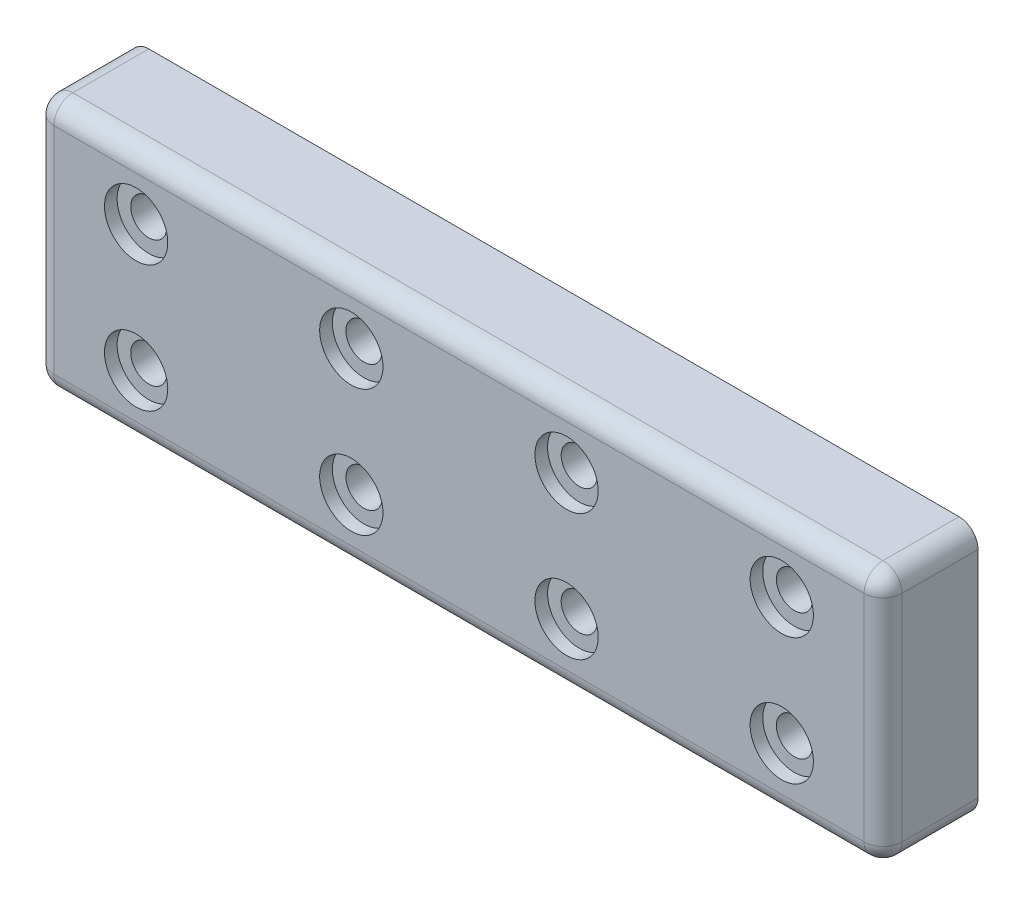
SolidWorks part; units mm, degrees
ref_plane "Front Plane" through (0, 0, 0) normal (0, 0, 1) x (1, 0, 0)
ref_plane "Top Plane" through (0, 0, 0) normal (0, 1, 0) x (1, 0, 0)
ref_plane "Right Plane" through (0, 0, 0) normal (1, 0, 0) x (0, 0, -1)
sketch "Sketch1" plane through (0, 0, 0) normal (0, 0, 1) x (1, 0, 0)
  line L1 (-67, -20) -> (67, -20)
  line L2 (-67, -20) -> (-67, 20)
  line L3 (-67, 20) -> (67, 20)
  line L4 (67, -20) -> (67, 20)
  line L5 (-67, -20) -> (67, 20) construction
  line L6 (-67, 20) -> (67, -20) construction
  circle A0 centre (-51, 10) radius 2.85
  circle A1 centre (-17, 10) radius 2.85
  circle A2 centre (17, 10) radius 2.85
  circle A3 centre (51, 10) radius 2.85
  circle A4 centre (-17, -10) radius 2.85
  circle A5 centre (17, -10) radius 2.85
  circle A6 centre (51, -10) radius 2.85
  circle A7 centre (-51, -10) radius 2.85
  point P0 (0, 0)
  dimension "D3" = 5.7
  dimension "D1" = 134
  dimension "D2" = 40
  dimension "D4" = 10
  dimension "D5" = 16
  dimension "D6" = 4
  dimension "D7" = 2
extrude "Boss-Extrude1" add sketch "Sketch1" along normal blind 15
sketch "Sketch2" plane through (0, 0, 15) normal (0, 0, 1) x (1, 0, 0)
  circle A0 centre (-51, 10) radius 5
  circle A1 centre (-17, 10) radius 5
  circle A2 centre (17, 10) radius 5
  circle A3 centre (51, 10) radius 5
  circle A4 centre (-17, -10) radius 5
  circle A5 centre (17, -10) radius 5
  circle A6 centre (51, -10) radius 5
  circle A7 centre (-51, -10) radius 5
  dimension "D1" = 10
  dimension "D2" = 4
  dimension "D3" = 2
extrude "Cut-Extrude1" cut sketch "Sketch2" against normal blind 2
fillet "Fillet1" radius 3 8 edges at (-67, 20, 7.5) (-67, -20, 7.5) (67, -20, 7.5) (67, 20, 7.5) (67, 0, 15) (0, -20, 15) (-67, 0, 15) (0, 20, 15)
